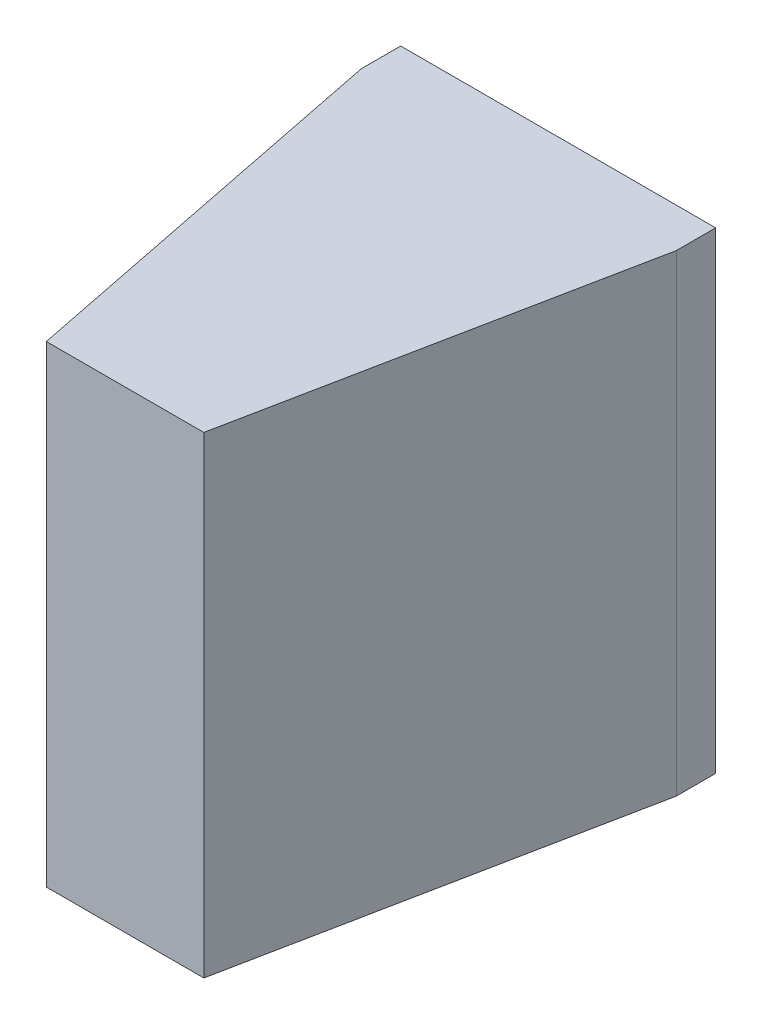
SolidWorks part; units mm, degrees
ref_plane "Front Plane" through (0, 0, 0) normal (0, 0, 1) x (1, 0, 0)
ref_plane "Top Plane" through (0, 0, 0) normal (0, 1, 0) x (1, 0, 0)
ref_plane "Right Plane" through (0, 0, 0) normal (1, 0, 0) x (0, 0, -1)
sketch "Sketch1" plane through (0, 0, 0) normal (0, 0, 1) x (1, 0, 0)
  line L1 (-40, -60) -> (40, -60)
  line L2 (-40, -60) -> (-40, 60)
  line L3 (-40, 60) -> (40, 60)
  line L4 (40, -60) -> (40, 60)
  line L5 (-40, -60) -> (40, 60) construction
  line L6 (-40, 60) -> (40, -60) construction
  point P0 (0, 0)
  dimension "D1" = 120
  dimension "D2" = 80
extrude "Boss-Extrude1" add sketch "Sketch1" along normal blind 10
sketch "Sketch2" plane through (0, 0, 0) normal (0, 1, 0) x (1, 0, 0)
  line L0 (0, -10) -> (0, -110) construction
  line L1 (40, -10) -> (-40, -10) construction
  line L2 (40, -10) -> (-40, -10)
  line L3 (-40, -10) -> (-20, -110)
  line L4 (-20, -110) -> (20, -110)
  line L5 (40, -10) -> (20, -110)
  dimension "D1" = 100
  dimension "D2" = 20
extrude "Boss-Extrude2" add sketch "Sketch2" along normal mid plane 120
sketch "Sketch3" plane through (0, 0, 0) normal (0, 1, 0) x (1, 0, 0)
  line L0 (40, -10) -> (-40, -10)
  line L1 (-40, -10) -> (-40, -100)
  line L2 (-40, -100) -> (40, -100)
  line L3 (40, -100) -> (40, -10)
  line L4 (-20, -110) -> (20, -110) construction
  dimension "D1" = 10
